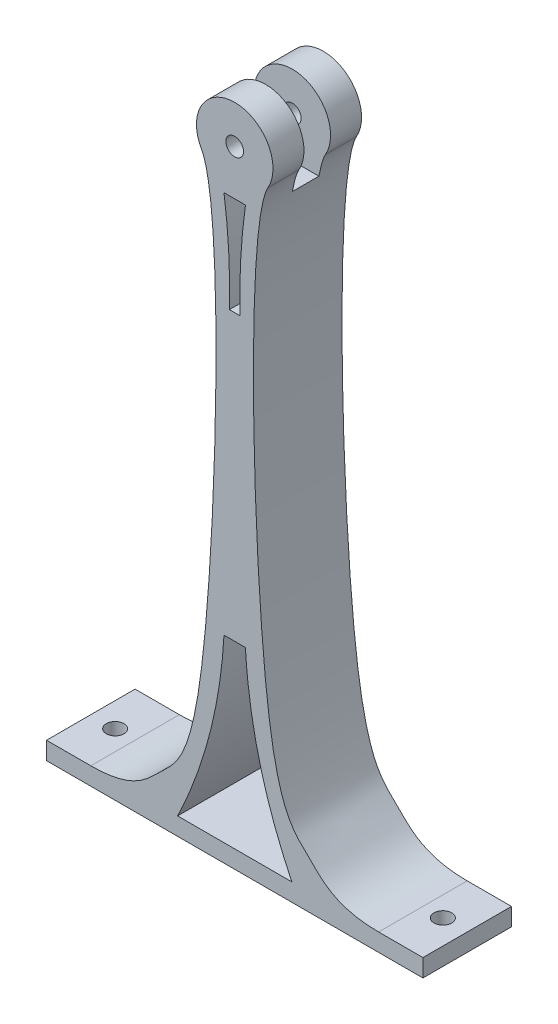
SolidWorks part; units mm, degrees
ref_plane "Alzado" through (0, 0, 0) normal (0, 0, 1) x (1, 0, 0)
ref_plane "Planta" through (0, 0, 0) normal (0, 1, 0) x (1, 0, 0)
ref_plane "Vista lateral" through (0, 0, 0) normal (1, 0, 0) x (0, 0, -1)
sketch "Croquis1" plane through (0, 0, 0) normal (0, 0, 1) x (1, 0, 0)
  line L0 (0, 0) -> (0, 150) construction
  line L1 (-42.5, 0) -> (-42.5, 4)
  line L2 (-42.5, 4) -> (-32.5, 4)
  line L3 (-42.5, 0) -> (42.5, 0)
  line L4 (42.5, 4) -> (32.5, 4)
  line L6 (42.5, 0) -> (42.5, 4)
  arc A0 (-7.5, 137.0639) -> (7.5, 137.0639) centre (0, 141.3578) cw
  spline S0 degree 3 poles (-32.5, 4) (-22.6706, 4) (-16.227, 12.3012) (-5.1224, 19.1144) (-2.3643, 128.0935) (-7.5, 137.0639) knots 0 0 0 0 0.229195 0.488953 0.855765 0.855765 0.855765 0.855765
  spline S1 degree 3 poles (32.5, 4) (22.6706, 4) (16.227, 12.3012) (5.1224, 19.1144) (2.3643, 128.0935) (7.5, 137.0639) knots 0 0 0 0 0.229195 0.488953 0.855765 0.855765 0.855765 0.855765
  dimension "D1" = 150
  dimension "D6" = 15
  dimension "D2" = 4
  dimension "D3" = 10
  dimension "D4" = 85
extrude "Saliente-Extruir2" add sketch "Croquis1" along normal blind 20
sketch "Croquis3" plane through (0, 0, 20) normal (0, 0, 1) x (1, 0, 0)
  line L0 (0, 0) -> (0, 141.3578) construction
  line L1 (-2.4216, 44.5914) -> (2.4216, 44.5914)
  line L2 (-2.4216, 131.1269) -> (2.4216, 131.1269)
  line L3 (-12.8962, 4) -> (12.8962, 4)
  line L4 (-32.5, 4) -> (-42.5, 4) construction
  line L5 (-42.5, 0) -> (42.5, 0) construction
  line L6 (-1.2108, 108.8605) -> (1.2108, 108.8605)
  circle A0 centre (0, 141.3578) radius 2
  arc A1 (7.5, 137.0639) -> (-7.5, 137.0639) centre (0, 141.3578) ccw construction
  spline S0 degree 2 poles (-12.8962, 4) (-3.6034, 23.1884) (-2.4216, 44.5914) knots 0 0 0 1 1 1
  spline S1 degree 2 poles (12.8962, 4) (3.6034, 23.1884) (2.4216, 44.5914) knots 0 0 0 1 1 1
  spline S4 degree 2 poles (-2.4216, 131.1269) (-0.8769, 120.0333) (-1.2108, 108.8605) knots 0 0 0 1 1 1
  spline S5 degree 2 poles (2.4216, 131.1269) (0.8769, 120.0333) (1.2108, 108.8605) knots 0 0 0 1 1 1
  point P9 (0, 108.8605)
  point P10 (0, 44.5914)
  point P15 (0, 104.0531)
  point P17 (0, 4)
  point P26 (0, 150)
  point P29 (0, 131.1269)
  dimension "D1" = 4
  dimension "D2" = 8.6422
  dimension "D3" = 141.3578
extrude "Cortar-Extruir1" cut sketch "Croquis3" against normal through all
sketch "Croquis6" plane through (0, 4, 0) normal (0, 1, 0) x (1, 0, 0)
  line L0 (42.5, -10) -> (-42.5, -10) construction
  line L1 (42.5, -20) -> (42.5, 0) construction
  line L2 (-42.5, -20) -> (-42.5, 0) construction
  line L3 (0, -10) -> (0, 10.7282) construction
  circle A0 centre (-37, -10) radius 2
  circle A1 centre (37, -10) radius 2
  dimension "D1" = 4
  dimension "D2" = 74
ref_plane "Plano1" through (0, 137.0639, 0) normal (0, -1, 0) x (-1, 0, 0)
sketch "Croquis7" plane through (0, 137.0639, 0) normal (0, -1, 0) x (-1, 0, 0)
  line L0 (42.5, -10) -> (-42.5, -10) construction
  line L1 (42.5, -20) -> (42.5, 0) construction
  line L2 (-42.5, -20) -> (-42.5, 0) construction
  line L3 (0, 0) -> (0, -20) construction
  line L4 (-8.6422, -20) -> (8.6422, -20) construction
  line L6 (-15, -7) -> (15, -7)
  line L7 (-15, -7) -> (-15, -13)
  line L8 (-15, -13) -> (15, -13)
  line L9 (15, -7) -> (15, -13)
  line L10 (-15, -7) -> (15, -13) construction
  line L11 (-15, -13) -> (15, -7) construction
  point P11 (0, -10)
  dimension "D1" = 30
  dimension "D2" = 6
extrude "Cortar-Extruir4" cut sketch "Croquis7" against normal blind 15 contours L8 L9 L6 L7
sketch "Croquis8" plane through (0, 137.0639, 0) normal (0, 1, 0) x (1, 0, 0)
  line L1 (-8.6422, -7) -> (8.6422, -7)
  line L2 (-8.6422, -7) -> (-8.6422, -13)
  line L3 (-8.6422, -13) -> (8.6422, -13)
  line L4 (8.6422, -7) -> (8.6422, -13)
extrude "Cortar-Extruir5" cut sketch "Croquis8" against normal blind 5
extrude "Cortar-Extruir3" cut sketch "Croquis6" against normal through all
